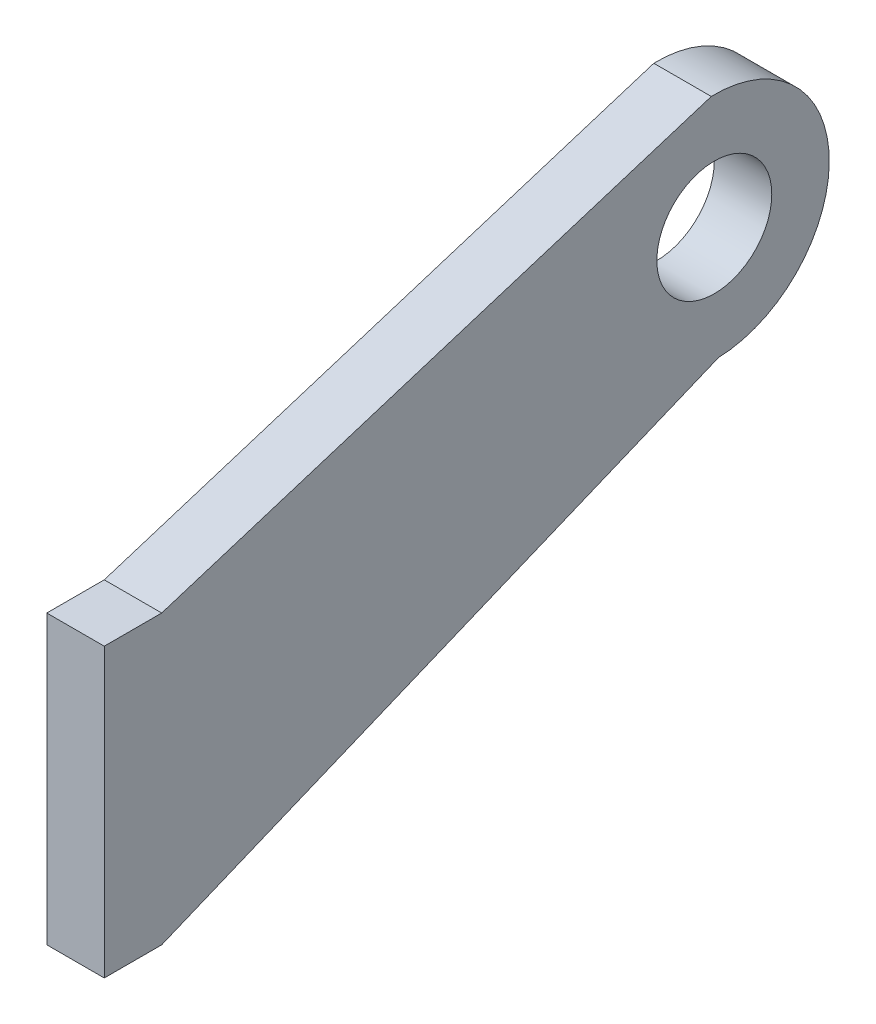
SolidWorks part; units mm, degrees
ref_plane "Front Plane" through (0, 0, 0) normal (0, 0, 1) x (1, 0, 0)
ref_plane "Top Plane" through (0, 0, 0) normal (0, 1, 0) x (1, 0, 0)
ref_plane "Right Plane" through (0, 0, 0) normal (1, 0, 0) x (0, 0, -1)
sketch "Sketch1" plane through (0, 0, 0) normal (1, 0, 0) x (0, 0, -1)
  line L1 (-0.0036, 4.4264) -> (19.1203, 10.4316)
  line L2 (-0.0036, -5.5736) -> (19.3695, 2.4355)
  line L4 (-0.0036, 4.4264) -> (-2.0036, 4.4264)
  line L6 (-0.0036, -5.5736) -> (-2.0036, -5.5736)
  line L7 (-2.0036, 4.4264) -> (-2.0036, -5.5736)
  circle A0 centre (19.2253, 6.4329) radius 2
  arc A1 (19.3695, 2.4355) -> (19.1203, 10.4316) centre (19.2253, 6.4329) ccw
  point P4 (0, 0)
  point P8 (-2.0036, 4.4264)
  point P9 (19.2253, 6.4329)
  dimension "D2" = 8
  dimension "D3" = 4
  dimension "D1" = 10
  dimension "D4" = 2
  dimension "D5" = 10
extrude "Boss-Extrude1" add sketch "Sketch1" along normal blind 2
